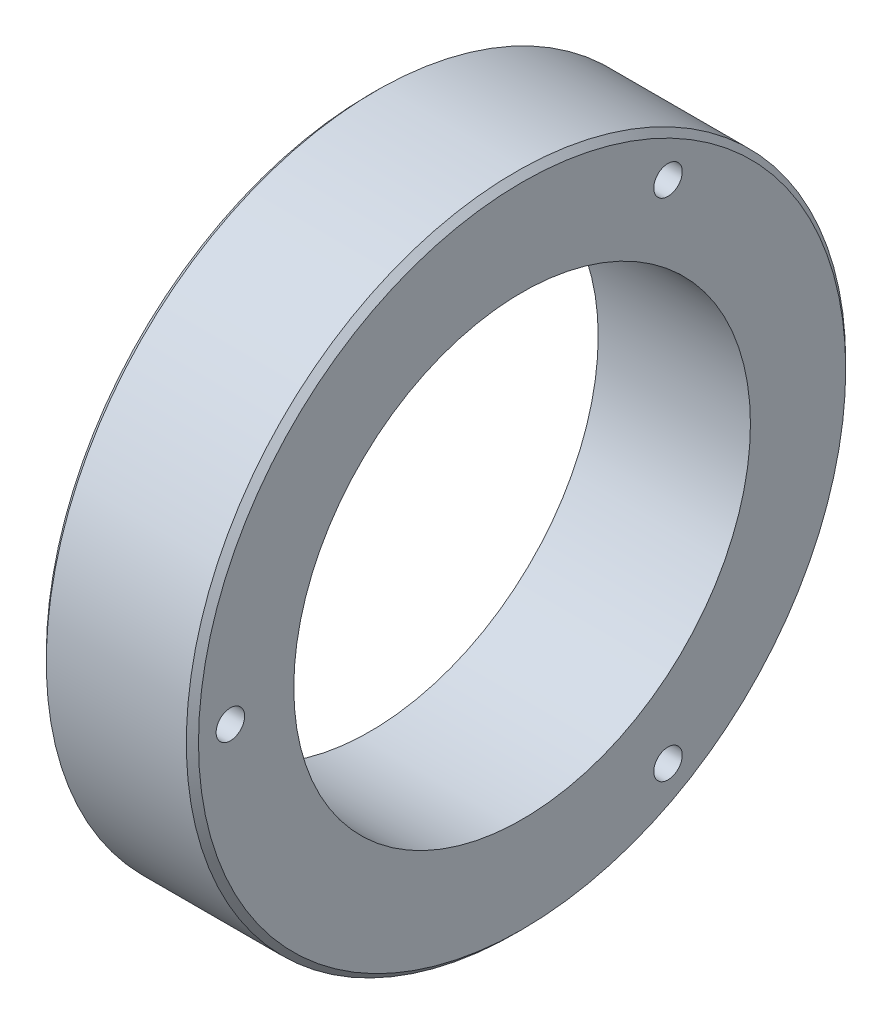
SolidWorks part; units mm, degrees
ref_plane "Front Plane" through (0, 0, 0) normal (1, 0, 0) x (0, 1, 0)
ref_plane "Top Plane" through (0, 0, 0) normal (0, 0, 1) x (0, 1, 0)
ref_plane "Right Plane" through (0, 0, 0) normal (0, 1, 0) x (-1, 0, 0)
sketch "Sketch1" plane through (0, 0, 0) normal (1, 0, 0) x (0, 1, 0)
  circle A0 centre (0, 0) radius 82.5246
extrude "Boss-Extrude1" add sketch "Sketch1" along normal blind 38.1
sketch "Sketch2" plane through (0, 0, 0) normal (1, 0, 0) x (0, 1, 0)
  circle A0 centre (0, 0) radius 57.15
extrude "Cut-Extrude1" cut sketch "Sketch2" along normal blind 38.1
sketch "Sketch3" plane through (0, 0, 0) normal (1, 0, 0) x (0, 1, 0)
  circle A0 centre (0, 73.025) radius 3.5687
  circle A1 centre (-63.2415, -36.5125) radius 3.5687
  circle A2 centre (63.2415, -36.5125) radius 3.5687
extrude "Cut-Extrude3" cut sketch "Sketch3" along normal through all
sketch "Sketch4" plane through (0, 0, 0) normal (1, 0, 0) x (0, 1, 0)
  circle A0 centre (0, 73.025) radius 5.5626
  circle A1 centre (-63.2415, -36.5125) radius 5.5626
  circle A2 centre (63.2415, -36.5125) radius 5.5626
extrude "Cut-Extrude4" cut sketch "Sketch4" along normal blind 9.652
chamfer "Chamfer1" distance 1.524 angle 45 2 edges at (38.1, 0, -82.5246) (0, 0, -82.5246)
